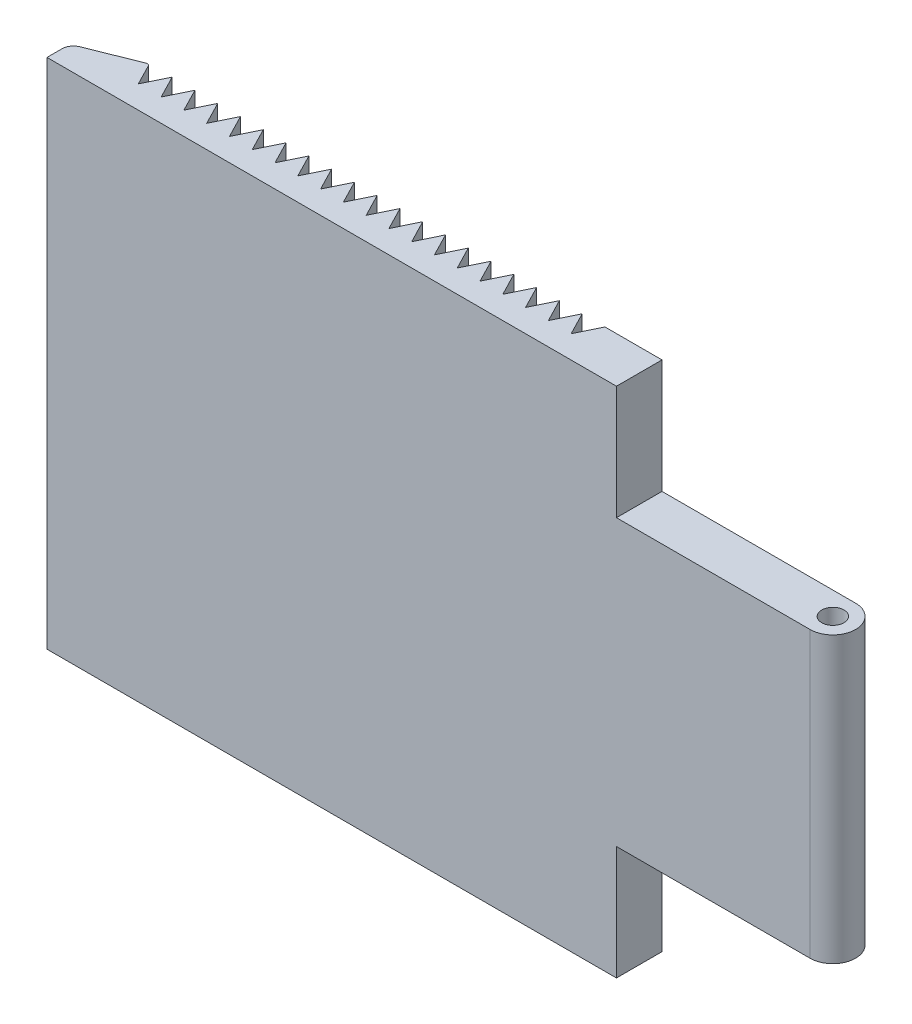
SolidWorks part; units mm, degrees
ref_plane "Ön Düzlem" through (0, 0, 0) normal (0, 0, 1) x (1, 0, 0)
ref_plane "Üst Düzlem" through (0, 0, 0) normal (0, 1, 0) x (1, 0, 0)
ref_plane "Sağ Düzlem" through (0, 0, 0) normal (1, 0, 0) x (0, 0, -1)
sketch "Sketch1" plane through (0, 0, 0) normal (0, 0, 1) x (1, 0, 0)
  line L1 (50, 45) -> (-50, 45)
  line L2 (50, 45) -> (50, 25)
  line L3 (50, -45) -> (-50, -45)
  line L4 (-50, 45) -> (-50, -45)
  line L7 (50, 25) -> (90, 25)
  line L9 (90, 25) -> (90, -25)
  line L14 (90, 0) -> (131.1465, 0) construction
  line L16 (50, -25) -> (90, -25)
  line L18 (50, -25) -> (50, -45)
  point P0 (0, 0)
  point P9 (50, 0)
  dimension "D1" = 100
  dimension "D2" = 90
  dimension "D3" = 50
extrude "Boss-Extrude1" add sketch "Sketch1" along normal blind 8
sketch "Sketch2" plane through (0, 25, 0) normal (0, 1, 0) x (1, 0, 0)
  line L0 (90, -8) -> (90, 0) construction
  line L1 (90, -8) -> (50, -8) construction
  circle A0 centre (84, -4) radius 1.95
  dimension "D1" = 6
  dimension "D2" = 4
extrude "Cut-Extrude1" cut sketch "Sketch2" against normal blind 150
sketch "Sketch3" plane through (0, 25, 0) normal (0, 1, 0) x (1, 0, 0)
  line L0 (90, -8) -> (50, -8) construction
  line L1 (90, -8) -> (90, 0) construction
  line L2 (90, 0) -> (50, 0) construction
  line L3 (90, -8) -> (84, -8)
  line L4 (90, -8) -> (90, 0)
  line L5 (90, 0) -> (84, 0)
  arc A0 (84, 0) -> (84, -8) centre (84, -4) cw
extrude "Cut-Extrude2" cut sketch "Sketch3" against normal blind 150
sketch "Sketch4" plane through (0, 45, 0) normal (0, 1, 0) x (1, 0, 0)
  line L0 (-50, -4) -> (-40.0186, 0)
  line L1 (-50, -8) -> (-50, 0) construction
  line L2 (50, 0) -> (-50, 0) construction
  line L3 (-40.0186, 0) -> (-37.957, -4)
  line L4 (-37.957, -4) -> (-36.0186, 0)
  line L5 (-50, -4) -> (50, -4) construction
  line L6 (50, -8) -> (50, 0) construction
  line L7 (-36.0186, 0) -> (-33.957, -4)
  line L8 (-33.957, -4) -> (-32.0186, 0)
  line L9 (-32.0186, 0) -> (-29.957, -4)
  line L10 (-29.957, -4) -> (-28.0186, 0)
  line L11 (-28.0186, 0) -> (-25.957, -4)
  line L12 (-25.957, -4) -> (-24.0186, 0)
  line L13 (-24.0186, 0) -> (-21.957, -4)
  line L14 (-21.957, -4) -> (-20.0186, 0)
  line L15 (-20.0186, 0) -> (-17.957, -4)
  line L16 (-17.957, -4) -> (-16.0186, 0)
  line L17 (-16.0186, 0) -> (-13.957, -4)
  line L18 (-13.957, -4) -> (-12.0186, 0)
  line L19 (-12.0186, 0) -> (-9.957, -4)
  line L20 (-9.957, -4) -> (-8.0186, 0)
  line L21 (-8.0186, 0) -> (-5.957, -4)
  line L22 (-5.957, -4) -> (-4.0186, 0)
  line L23 (-4.0186, 0) -> (-1.957, -4)
  line L24 (-1.957, -4) -> (-0.0186, 0)
  line L25 (-0.0186, 0) -> (2.043, -4)
  line L26 (2.043, -4) -> (3.9814, 0)
  line L27 (3.9814, 0) -> (6.043, -4)
  line L28 (6.043, -4) -> (7.9814, 0)
  line L29 (7.9814, 0) -> (10.043, -4)
  line L30 (10.043, -4) -> (11.9814, 0)
  line L31 (11.9814, 0) -> (14.043, -4)
  line L32 (14.043, -4) -> (15.9814, 0)
  line L33 (15.9814, 0) -> (18.043, -4)
  line L34 (18.043, -4) -> (19.9814, 0)
  line L35 (19.9814, 0) -> (22.043, -4)
  line L36 (22.043, -4) -> (23.9814, 0)
  line L37 (23.9814, 0) -> (26.043, -4)
  line L38 (26.043, -4) -> (27.9814, 0)
  line L39 (27.9814, 0) -> (30.043, -4)
  line L40 (30.043, -4) -> (31.9814, 0)
  line L41 (31.9814, 0) -> (34.043, -4)
  line L42 (34.043, -4) -> (35.9814, 0)
  line L43 (35.9814, 0) -> (38.043, -4)
  line L44 (38.043, -4) -> (39.9814, 0)
  line L45 (-50, -4) -> (-50, 0)
  line L47 (-50, 0) -> (-31.2679, 8.1878)
  line L48 (-31.2679, 8.1878) -> (37.1593, 4.6205)
  line L49 (37.1593, 4.6205) -> (39.9814, 0)
  dimension "D1" = 4
  dimension "D2" = 20
extrude "Cut-Extrude3" cut sketch "Sketch4" against normal blind 150
fillet "Fillet2" radius 0.5 1 edges at (-40.0186, 0, 0)
fillet "Fillet3" radius 2 1 edges at (-50, 0, 4)
